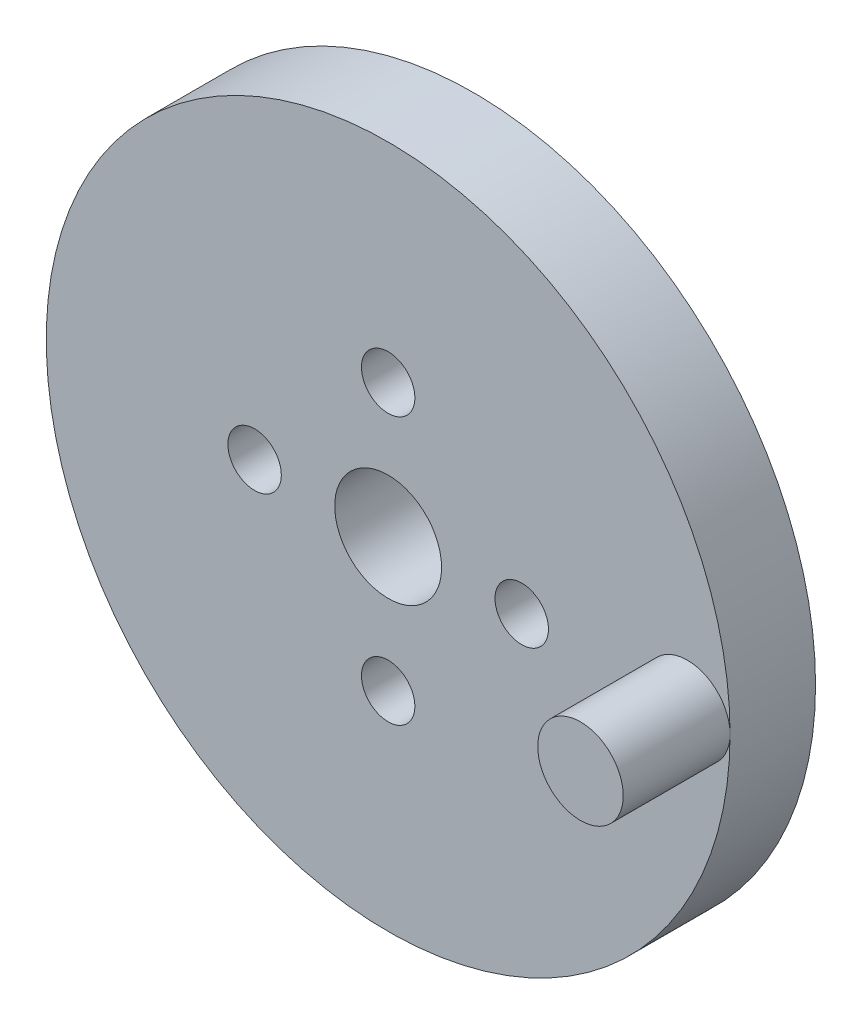
SolidWorks part; units mm, degrees
ref_plane "Plan de face" through (0, 0, 0) normal (0, 0, 1) x (1, 0, 0)
ref_plane "Plan de dessus" through (0, 0, 0) normal (0, 1, 0) x (1, 0, 0)
ref_plane "Plan de droite" through (0, 0, 0) normal (1, 0, 0) x (0, 0, -1)
sketch "Croquis1" plane through (0, 0, 0) normal (0, 0, 1) x (1, 0, 0)
  circle A0 centre (0, 0) radius 32
  circle A1 centre (0, 0) radius 5
  dimension "D1" = 64
  dimension "D2" = 10
extrude "Saliente-Extruir1" add sketch "Croquis1" along normal blind 8
sketch "Croquis3" plane through (0, 0, 0) normal (0, 0, -1) x (-1, 0, 0)
  circle A0 centre (0, 0) radius 12.5 construction
  circle A1 centre (12.5, 0) radius 2.5
  circle A2 centre (0, -12.5) radius 2.5
  circle A3 centre (-12.5, 0) radius 2.5
  circle A4 centre (0, 12.5) radius 2.5
  point P14 (0, 0)
  dimension "D1" = 25
  dimension "D2" = 5
  dimension "D3" = 4
extrude "Cortar-Extruir1" cut sketch "Croquis3" against normal blind 10
sketch "Croquis4" plane through (0, 0, 8) normal (0, 0, 1) x (1, 0, 0)
  circle A0 centre (28, 0) radius 4
  circle A1 centre (0, 0) radius 32 construction
  point P2 (0, 0)
  dimension "D1" = 8
extrude "Saliente-Extruir2" add sketch "Croquis4" along normal blind 10
